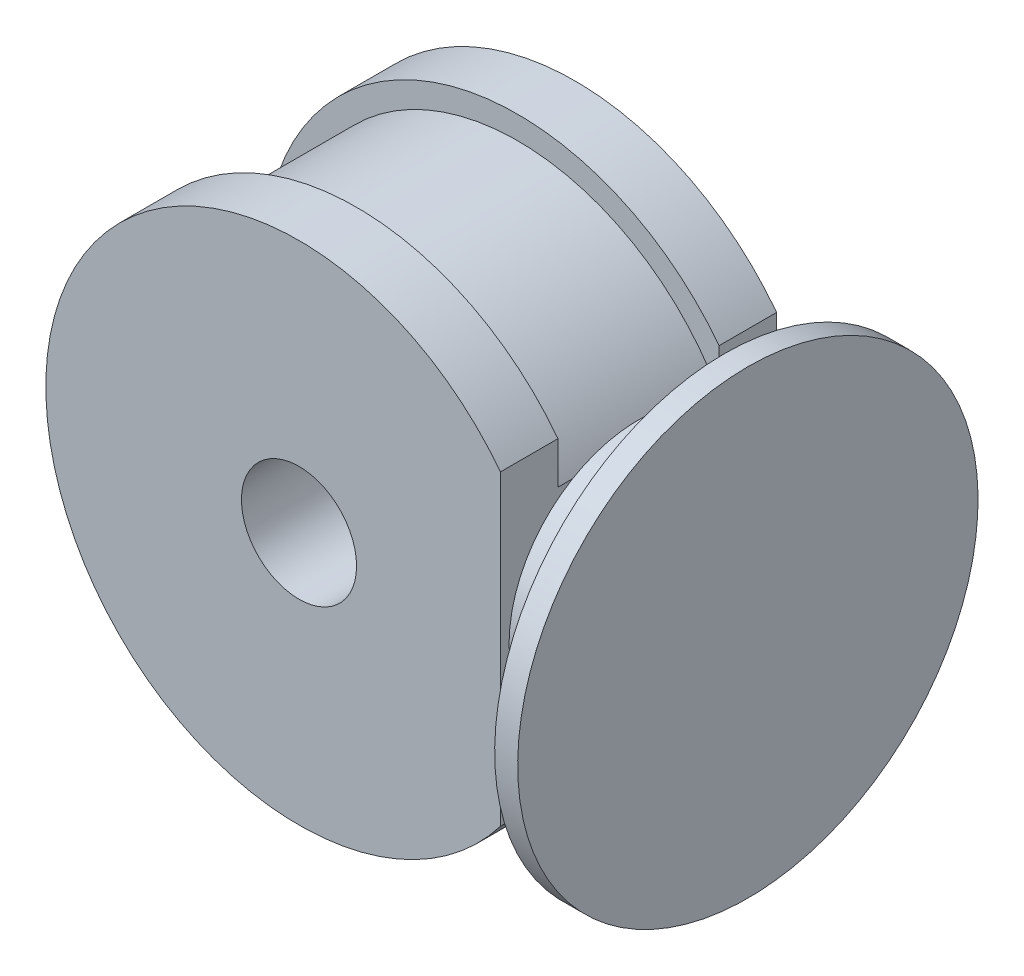
SolidWorks part; units mm, degrees
ref_plane "Plan de face" through (0, 0, 0) normal (0, 0, 1) x (1, 0, 0)
ref_plane "Plan de dessus" through (0, 0, 0) normal (0, 1, 0) x (1, 0, 0)
ref_plane "Plan de droite" through (0, 0, 0) normal (1, 0, 0) x (0, 0, -1)
sketch "Esquisse1" plane through (0, 0, 0) normal (0, 0, 1) x (1, 0, 0)
  circle A0 centre (0, 0) radius 44
  dimension "D1" = 88
extrude "Boss.-Extru.1" add sketch "Esquisse1" along normal blind 10
sketch "Esquisse2" plane through (0, 0, 10) normal (0, 0, 1) x (1, 0, 0)
  circle A0 centre (0, 0) radius 40
  dimension "D1" = 80
extrude "Boss.-Extru.2" add sketch "Esquisse2" along normal blind 28
sketch "Esquisse3" plane through (0, 0, 38) normal (0, 0, 1) x (1, 0, 0)
  circle A0 centre (0, 0) radius 44
extrude "Boss.-Extru.3" add sketch "Esquisse3" along normal blind 10
sketch "Esquisse5" plane through (0, 0, 48) normal (0, 0, 1) x (1, 0, 0)
  line L1 (35, 44.0697) -> (67.4724, 44.0697)
  line L2 (35, 44.0697) -> (35, -50.6619)
  line L3 (35, -50.6619) -> (67.4724, -50.6619)
  line L4 (67.4724, 44.0697) -> (67.4724, -50.6619)
  dimension "D1" = 35
extrude "Enlèv. mat.-Extru.2" cut sketch "Esquisse5" against normal through all
sketch "Esquisse4" plane through (0, 0, 48) normal (0, 0, 1) x (1, 0, 0)
  circle A0 centre (0, 0) radius 10
  dimension "D1" = 20
extrude "Enlèv. mat.-Extru.1" cut sketch "Esquisse4" against normal through all
ref_point "Point1"
sketch "Sketch1" plane through (35, 0, 0) normal (1, 0, 0) x (0, 0, -1)
  circle A0 centre (-24, 0) radius 22.5
extrude "Boss-Extrude1" add sketch "Sketch1" along normal blind 15
sketch "Sketch2" plane through (50, 0, 0) normal (1, 0, 0) x (0, 0, -1)
  circle A0 centre (-24, 0) radius 40
  dimension "D1" = 80
extrude "Boss-Extrude2" add sketch "Sketch2" along normal blind 4
